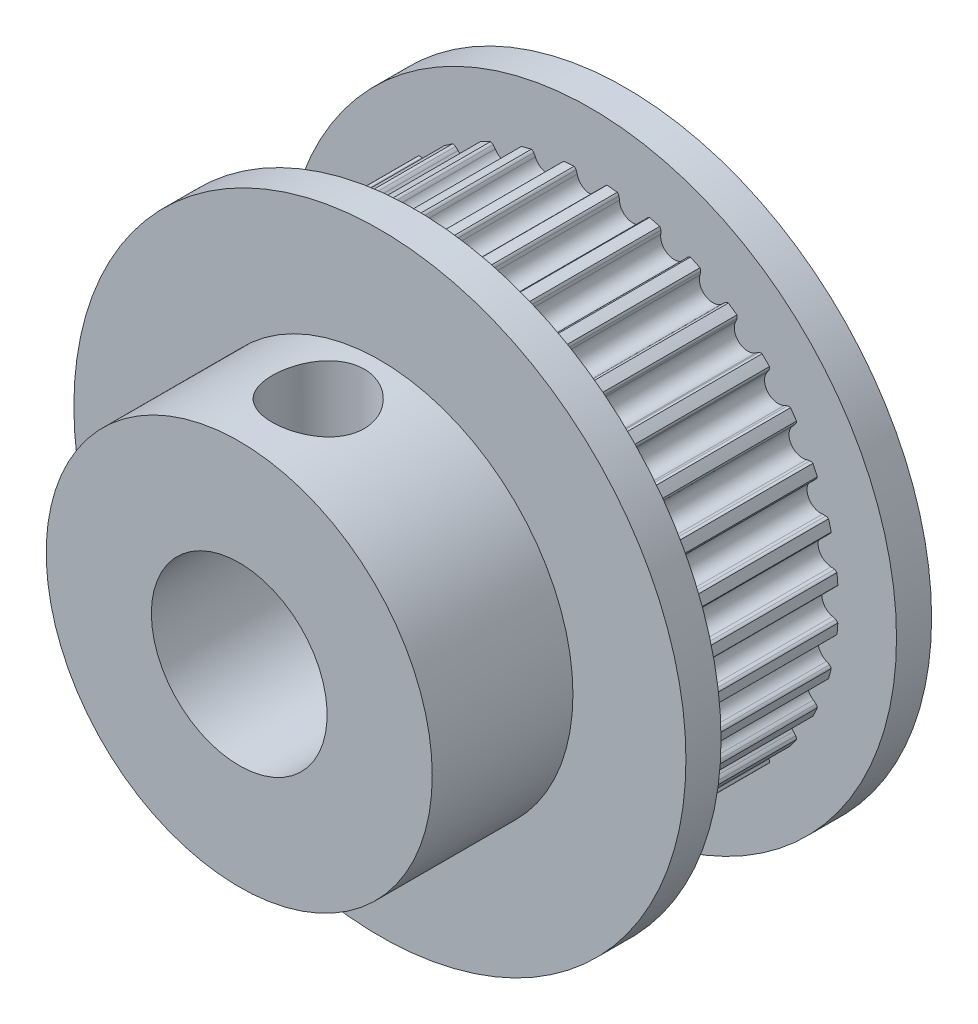
SolidWorks part; units mm, degrees
ref_plane "Front Plane" through (0, 0, 0) normal (0, 0, 1) x (1, 0, 0)
ref_plane "Top Plane" through (0, 0, 0) normal (0, 1, 0) x (1, 0, 0)
ref_plane "Right Plane" through (0, 0, 0) normal (1, 0, 0) x (0, 0, -1)
sketch "Sketch1" plane through (0, 0, 0) normal (0, 1, 0) x (1, 0, 0)
  line L0 (13.843, -3.9687) -> (0, -3.9687)
  line L1 (0, -3.9687) -> (0, -5.5562)
  line L2 (0, -5.5562) -> (13.843, -5.5562)
  line L3 (13.843, -5.5562) -> (13.843, -3.9687)
  line L4 (0, -3.9687) -> (0, -5.5562) construction
revolve "Revolve1" add sketch "Sketch1" angle 360 about L4
sketch "Sketch2" plane through (0, 0, 3.9687) normal (0, 0, -1) x (-1, 0, 0)
  arc A0 (-3.1309, 10.7682) -> (-2.6727, 10.891) centre (0, 0) cw
  arc A6 (-1.2134, 11.1483) -> (-0.7409, 11.1896) centre (0, 0) cw
  arc A7 (-4.5233, 10.2614) -> (-4.4045, 10.2) centre (-4.5654, 10.0341) cw
  arc A8 (-4.4045, 10.2) -> (-4.3083, 10.0819) centre (-4.8573, 9.7334) cw
  arc A9 (-4.3083, 10.0819) -> (-3.1801, 10.4925) centre (-3.7894, 10.4113) ccw
  arc A10 (-3.1801, 10.4925) -> (-3.1824, 10.6448) centre (-2.5356, 10.5784) cw
  arc A11 (-3.1824, 10.6448) -> (-3.1309, 10.7682) centre (-2.9525, 10.6212) cw
  arc A12 (-2.6727, 10.891) -> (-2.5663, 10.8099) centre (-2.7537, 10.6745) cw
  arc A13 (-2.5663, 10.8099) -> (-2.4922, 10.6768) centre (-3.0933, 10.429) cw
  arc A14 (-2.4922, 10.6768) -> (-1.3098, 10.8853) centre (-1.9239, 10.9112) ccw
  arc A15 (-1.3098, 10.8853) -> (-1.2856, 11.0357) centre (-0.6601, 10.858) cw
  arc A16 (-1.2856, 11.0357) -> (-1.2134, 11.1483) centre (-1.0633, 10.9725) cw
  arc A17 (-0.7409, 11.1896) -> (-0.6502, 11.0913) centre (-0.8582, 10.9905) cw
  arc A18 (-0.6502, 11.0913) -> (-0.6003, 10.9474) centre (-1.2354, 10.8077) cw
  arc A19 (-0.6003, 10.9474) -> (0.6003, 10.9474) centre (0, 11.0795) ccw
  arc A20 (0.6003, 10.9474) -> (0.6502, 11.0913) centre (1.2354, 10.8077) cw
  arc A21 (0.6502, 11.0913) -> (0.7409, 11.1896) centre (0.8582, 10.9905) cw
  arc A22 (1.2134, 11.1483) -> (1.2856, 11.0357) centre (1.0633, 10.9725) cw
  arc A23 (1.2856, 11.0357) -> (1.3098, 10.8853) centre (0.6601, 10.858) cw
  arc A24 (1.3098, 10.8853) -> (2.4922, 10.6768) centre (1.9239, 10.9112) ccw
  arc A25 (2.4922, 10.6768) -> (2.5663, 10.8099) centre (3.0933, 10.429) cw
  arc A26 (2.5663, 10.8099) -> (2.6727, 10.891) centre (2.7537, 10.6745) cw
  arc A27 (3.1309, 10.7682) -> (3.1824, 10.6448) centre (2.9525, 10.6212) cw
  arc A28 (3.1824, 10.6448) -> (3.1801, 10.4925) centre (2.5356, 10.5784) cw
  arc A29 (3.1801, 10.4925) -> (4.3083, 10.0819) centre (3.7894, 10.4113) ccw
  arc A30 (4.3083, 10.0819) -> (4.4045, 10.2) centre (4.8573, 9.7334) cw
  arc A31 (4.4045, 10.2) -> (4.5233, 10.2614) centre (4.5654, 10.0341) cw
  arc A32 (4.9532, 10.0609) -> (4.9825, 9.9305) centre (4.752, 9.9471) cw
  arc A33 (4.9825, 9.9305) -> (4.9538, 9.7809) centre (4.334, 9.9774) cw
  arc A34 (4.9538, 9.7809) -> (5.9936, 9.1806) centre (5.5397, 9.5951) ccw
  arc A35 (5.9936, 9.1806) -> (6.1088, 9.2802) centre (6.4737, 8.742) cw
  arc A36 (6.1088, 9.2802) -> (6.2364, 9.32) centre (6.2385, 9.0889) cw
  arc A37 (6.625, 9.048) -> (6.6312, 8.9144) centre (6.4071, 8.9709) cw
  arc A38 (6.6312, 8.9144) -> (6.577, 8.7721) centre (6.0007, 9.0732) cw
  arc A39 (6.577, 8.7721) -> (7.4967, 8.0003) centre (7.1218, 8.4874) ccw
  arc A40 (7.4967, 8.0003) -> (7.6275, 8.0784) centre (7.8934, 7.4851) cw
  arc A41 (7.6275, 8.0784) -> (7.7601, 8.0955) centre (7.722, 7.8675) cw
  arc A42 (8.0955, 7.7601) -> (8.0784, 7.6275) centre (7.8675, 7.722) cw
  arc A43 (8.0784, 7.6275) -> (8.0003, 7.4967) centre (7.4851, 7.8934) cw
  arc A44 (8.0003, 7.4967) -> (8.7721, 6.577) centre (8.4874, 7.1218) ccw
  arc A45 (8.7721, 6.577) -> (8.9144, 6.6312) centre (9.0732, 6.0007) cw
  arc A46 (8.9144, 6.6312) -> (9.048, 6.625) centre (8.9709, 6.4071) cw
  arc A47 (9.32, 6.2364) -> (9.2802, 6.1088) centre (9.0889, 6.2385) cw
  arc A48 (9.2802, 6.1088) -> (9.1806, 5.9936) centre (8.742, 6.4737) cw
  arc A49 (9.1806, 5.9936) -> (9.7809, 4.9538) centre (9.5951, 5.5397) ccw
  arc A50 (9.7809, 4.9538) -> (9.9305, 4.9825) centre (9.9774, 4.334) cw
  arc A51 (9.9305, 4.9825) -> (10.0609, 4.9532) centre (9.9471, 4.752) cw
  arc A52 (10.2614, 4.5233) -> (10.2, 4.4045) centre (10.0341, 4.5654) cw
  arc A53 (10.2, 4.4045) -> (10.0819, 4.3083) centre (9.7334, 4.8573) cw
  arc A54 (10.0819, 4.3083) -> (10.4925, 3.1801) centre (10.4113, 3.7894) ccw
  arc A55 (10.4925, 3.1801) -> (10.6448, 3.1824) centre (10.5784, 2.5356) cw
  arc A56 (10.6448, 3.1824) -> (10.7682, 3.1309) centre (10.6212, 2.9525) cw
  arc A57 (10.891, 2.6727) -> (10.8099, 2.5663) centre (10.6745, 2.7537) cw
  arc A58 (10.8099, 2.5663) -> (10.6768, 2.4922) centre (10.429, 3.0933) cw
  arc A59 (10.6768, 2.4922) -> (10.8853, 1.3098) centre (10.9112, 1.9239) ccw
  arc A60 (10.8853, 1.3098) -> (11.0357, 1.2856) centre (10.858, 0.6601) cw
  arc A61 (11.0357, 1.2856) -> (11.1483, 1.2134) centre (10.9725, 1.0633) cw
  arc A62 (11.1896, 0.7409) -> (11.0913, 0.6502) centre (10.9905, 0.8582) cw
  arc A63 (11.0913, 0.6502) -> (10.9474, 0.6003) centre (10.8077, 1.2354) cw
  arc A64 (10.9474, 0.6003) -> (10.9474, -0.6003) centre (11.0795, 0) ccw
  arc A65 (10.9474, -0.6003) -> (11.0913, -0.6502) centre (10.8077, -1.2354) cw
  arc A66 (11.0913, -0.6502) -> (11.1896, -0.7409) centre (10.9905, -0.8582) cw
  arc A67 (11.1483, -1.2134) -> (11.0357, -1.2856) centre (10.9725, -1.0633) cw
  arc A68 (11.0357, -1.2856) -> (10.8853, -1.3098) centre (10.858, -0.6601) cw
  arc A69 (10.8853, -1.3098) -> (10.6768, -2.4922) centre (10.9112, -1.9239) ccw
  arc A70 (10.6768, -2.4922) -> (10.8099, -2.5663) centre (10.429, -3.0933) cw
  arc A71 (10.8099, -2.5663) -> (10.891, -2.6727) centre (10.6745, -2.7537) cw
  arc A72 (10.7682, -3.1309) -> (10.6448, -3.1824) centre (10.6212, -2.9525) cw
  arc A73 (10.6448, -3.1824) -> (10.4925, -3.1801) centre (10.5784, -2.5356) cw
  arc A74 (10.4925, -3.1801) -> (10.0819, -4.3083) centre (10.4113, -3.7894) ccw
  arc A75 (10.0819, -4.3083) -> (10.2, -4.4045) centre (9.7334, -4.8573) cw
  arc A76 (10.2, -4.4045) -> (10.2614, -4.5233) centre (10.0341, -4.5654) cw
  arc A77 (10.0609, -4.9532) -> (9.9305, -4.9825) centre (9.9471, -4.752) cw
  arc A78 (9.9305, -4.9825) -> (9.7809, -4.9538) centre (9.9774, -4.334) cw
  arc A79 (9.7809, -4.9538) -> (9.1806, -5.9936) centre (9.5951, -5.5397) ccw
  arc A80 (9.1806, -5.9936) -> (9.2802, -6.1088) centre (8.742, -6.4737) cw
  arc A81 (9.2802, -6.1088) -> (9.32, -6.2364) centre (9.0889, -6.2385) cw
  arc A82 (9.048, -6.625) -> (8.9144, -6.6312) centre (8.9709, -6.4071) cw
  arc A83 (8.9144, -6.6312) -> (8.7721, -6.577) centre (9.0732, -6.0007) cw
  arc A84 (8.7721, -6.577) -> (8.0003, -7.4967) centre (8.4874, -7.1218) ccw
  arc A85 (8.0003, -7.4967) -> (8.0784, -7.6275) centre (7.4851, -7.8934) cw
  arc A86 (8.0784, -7.6275) -> (8.0955, -7.7601) centre (7.8675, -7.722) cw
  arc A87 (7.7601, -8.0955) -> (7.6275, -8.0784) centre (7.722, -7.8675) cw
  arc A88 (7.6275, -8.0784) -> (7.4967, -8.0003) centre (7.8934, -7.4851) cw
  arc A89 (7.4967, -8.0003) -> (6.577, -8.7721) centre (7.1218, -8.4874) ccw
  arc A90 (6.577, -8.7721) -> (6.6312, -8.9144) centre (6.0007, -9.0732) cw
  arc A91 (6.6312, -8.9144) -> (6.625, -9.048) centre (6.4071, -8.9709) cw
  arc A92 (6.2364, -9.32) -> (6.1088, -9.2802) centre (6.2385, -9.0889) cw
  arc A93 (6.1088, -9.2802) -> (5.9936, -9.1806) centre (6.4737, -8.742) cw
  arc A94 (5.9936, -9.1806) -> (4.9538, -9.7809) centre (5.5397, -9.5951) ccw
  arc A95 (4.9538, -9.7809) -> (4.9825, -9.9305) centre (4.334, -9.9774) cw
  arc A96 (4.9825, -9.9305) -> (4.9532, -10.0609) centre (4.752, -9.9471) cw
  arc A97 (4.5233, -10.2614) -> (4.4045, -10.2) centre (4.5654, -10.0341) cw
  arc A98 (4.4045, -10.2) -> (4.3083, -10.0819) centre (4.8573, -9.7334) cw
  arc A99 (4.3083, -10.0819) -> (3.1801, -10.4925) centre (3.7894, -10.4113) ccw
  arc A100 (3.1801, -10.4925) -> (3.1824, -10.6448) centre (2.5356, -10.5784) cw
  arc A101 (3.1824, -10.6448) -> (3.1309, -10.7682) centre (2.9525, -10.6212) cw
  arc A102 (2.6727, -10.891) -> (2.5663, -10.8099) centre (2.7537, -10.6745) cw
  arc A103 (2.5663, -10.8099) -> (2.4922, -10.6768) centre (3.0933, -10.429) cw
  arc A104 (2.4922, -10.6768) -> (1.3098, -10.8853) centre (1.9239, -10.9112) ccw
  arc A105 (1.3098, -10.8853) -> (1.2856, -11.0357) centre (0.6601, -10.858) cw
  arc A106 (1.2856, -11.0357) -> (1.2134, -11.1483) centre (1.0633, -10.9725) cw
  arc A107 (0.7409, -11.1896) -> (0.6502, -11.0913) centre (0.8582, -10.9905) cw
  arc A108 (0.6502, -11.0913) -> (0.6003, -10.9474) centre (1.2354, -10.8077) cw
  arc A109 (0.6003, -10.9474) -> (-0.6003, -10.9474) centre (0, -11.0795) ccw
  arc A110 (-0.6003, -10.9474) -> (-0.6502, -11.0913) centre (-1.2354, -10.8077) cw
  arc A111 (-0.6502, -11.0913) -> (-0.7409, -11.1896) centre (-0.8582, -10.9905) cw
  arc A112 (-1.2134, -11.1483) -> (-1.2856, -11.0357) centre (-1.0633, -10.9725) cw
  arc A113 (-1.2856, -11.0357) -> (-1.3098, -10.8853) centre (-0.6601, -10.858) cw
  arc A114 (-1.3098, -10.8853) -> (-2.4922, -10.6768) centre (-1.9239, -10.9112) ccw
  arc A115 (-2.4922, -10.6768) -> (-2.5663, -10.8099) centre (-3.0933, -10.429) cw
  arc A116 (-2.5663, -10.8099) -> (-2.6727, -10.891) centre (-2.7537, -10.6745) cw
  arc A117 (-3.1309, -10.7682) -> (-3.1824, -10.6448) centre (-2.9525, -10.6212) cw
  arc A118 (-3.1824, -10.6448) -> (-3.1801, -10.4925) centre (-2.5356, -10.5784) cw
  arc A119 (-3.1801, -10.4925) -> (-4.3083, -10.0819) centre (-3.7894, -10.4113) ccw
  arc A120 (-4.3083, -10.0819) -> (-4.4045, -10.2) centre (-4.8573, -9.7334) cw
  arc A121 (-4.4045, -10.2) -> (-4.5233, -10.2614) centre (-4.5654, -10.0341) cw
  arc A122 (-4.9532, -10.0609) -> (-4.9825, -9.9305) centre (-4.752, -9.9471) cw
  arc A123 (-4.9825, -9.9305) -> (-4.9538, -9.7809) centre (-4.334, -9.9774) cw
  arc A124 (-4.9538, -9.7809) -> (-5.9936, -9.1806) centre (-5.5397, -9.5951) ccw
  arc A125 (-5.9936, -9.1806) -> (-6.1088, -9.2802) centre (-6.4737, -8.742) cw
  arc A126 (-6.1088, -9.2802) -> (-6.2364, -9.32) centre (-6.2385, -9.0889) cw
  arc A127 (-6.625, -9.048) -> (-6.6312, -8.9144) centre (-6.4071, -8.9709) cw
  arc A128 (-6.6312, -8.9144) -> (-6.577, -8.7721) centre (-6.0007, -9.0732) cw
  arc A129 (-6.577, -8.7721) -> (-7.4967, -8.0003) centre (-7.1218, -8.4874) ccw
  arc A130 (-7.4967, -8.0003) -> (-7.6275, -8.0784) centre (-7.8934, -7.4851) cw
  arc A131 (-7.6275, -8.0784) -> (-7.7601, -8.0955) centre (-7.722, -7.8675) cw
  arc A132 (-8.0955, -7.7601) -> (-8.0784, -7.6275) centre (-7.8675, -7.722) cw
  arc A133 (-8.0784, -7.6275) -> (-8.0003, -7.4967) centre (-7.4851, -7.8934) cw
  arc A134 (-8.0003, -7.4967) -> (-8.7721, -6.577) centre (-8.4874, -7.1218) ccw
  arc A135 (-8.7721, -6.577) -> (-8.9144, -6.6312) centre (-9.0732, -6.0007) cw
  arc A136 (-8.9144, -6.6312) -> (-9.048, -6.625) centre (-8.9709, -6.4071) cw
  arc A137 (-9.32, -6.2364) -> (-9.2802, -6.1088) centre (-9.0889, -6.2385) cw
  arc A138 (-9.2802, -6.1088) -> (-9.1806, -5.9936) centre (-8.742, -6.4737) cw
  arc A139 (-9.1806, -5.9936) -> (-9.7809, -4.9538) centre (-9.5951, -5.5397) ccw
  arc A140 (-9.7809, -4.9538) -> (-9.9305, -4.9825) centre (-9.9774, -4.334) cw
  arc A141 (-9.9305, -4.9825) -> (-10.0609, -4.9532) centre (-9.9471, -4.752) cw
  arc A142 (-10.2614, -4.5233) -> (-10.2, -4.4045) centre (-10.0341, -4.5654) cw
  arc A143 (-10.2, -4.4045) -> (-10.0819, -4.3083) centre (-9.7334, -4.8573) cw
  arc A144 (-10.0819, -4.3083) -> (-10.4925, -3.1801) centre (-10.4113, -3.7894) ccw
  arc A145 (-10.4925, -3.1801) -> (-10.6448, -3.1824) centre (-10.5784, -2.5356) cw
  arc A146 (-10.6448, -3.1824) -> (-10.7682, -3.1309) centre (-10.6212, -2.9525) cw
  arc A147 (-10.891, -2.6727) -> (-10.8099, -2.5663) centre (-10.6745, -2.7537) cw
  arc A148 (-10.8099, -2.5663) -> (-10.6768, -2.4922) centre (-10.429, -3.0933) cw
  arc A149 (-10.6768, -2.4922) -> (-10.8853, -1.3098) centre (-10.9112, -1.9239) ccw
  arc A150 (-10.8853, -1.3098) -> (-11.0357, -1.2856) centre (-10.858, -0.6601) cw
  arc A151 (-11.0357, -1.2856) -> (-11.1483, -1.2134) centre (-10.9725, -1.0633) cw
  arc A152 (-11.1896, -0.7409) -> (-11.0913, -0.6502) centre (-10.9905, -0.8582) cw
  arc A153 (-11.0913, -0.6502) -> (-10.9474, -0.6003) centre (-10.8077, -1.2354) cw
  arc A154 (-10.9474, -0.6003) -> (-10.9474, 0.6003) centre (-11.0795, 0) ccw
  arc A155 (-10.9474, 0.6003) -> (-11.0913, 0.6502) centre (-10.8077, 1.2354) cw
  arc A156 (-11.0913, 0.6502) -> (-11.1896, 0.7409) centre (-10.9905, 0.8582) cw
  arc A157 (-11.1483, 1.2134) -> (-11.0357, 1.2856) centre (-10.9725, 1.0633) cw
  arc A158 (-11.0357, 1.2856) -> (-10.8853, 1.3098) centre (-10.858, 0.6601) cw
  arc A159 (-10.8853, 1.3098) -> (-10.6768, 2.4922) centre (-10.9112, 1.9239) ccw
  arc A160 (-10.6768, 2.4922) -> (-10.8099, 2.5663) centre (-10.429, 3.0933) cw
  arc A161 (-10.8099, 2.5663) -> (-10.891, 2.6727) centre (-10.6745, 2.7537) cw
  arc A162 (-10.7682, 3.1309) -> (-10.6448, 3.1824) centre (-10.6212, 2.9525) cw
  arc A163 (-10.6448, 3.1824) -> (-10.4925, 3.1801) centre (-10.5784, 2.5356) cw
  arc A164 (-10.4925, 3.1801) -> (-10.0819, 4.3083) centre (-10.4113, 3.7894) ccw
  arc A165 (-10.0819, 4.3083) -> (-10.2, 4.4045) centre (-9.7334, 4.8573) cw
  arc A166 (-10.2, 4.4045) -> (-10.2614, 4.5233) centre (-10.0341, 4.5654) cw
  arc A167 (-10.0609, 4.9532) -> (-9.9305, 4.9825) centre (-9.9471, 4.752) cw
  arc A168 (-9.9305, 4.9825) -> (-9.7809, 4.9538) centre (-9.9774, 4.334) cw
  arc A169 (-9.7809, 4.9538) -> (-9.1806, 5.9936) centre (-9.5951, 5.5397) ccw
  arc A170 (-9.1806, 5.9936) -> (-9.2802, 6.1088) centre (-8.742, 6.4737) cw
  arc A171 (-9.2802, 6.1088) -> (-9.32, 6.2364) centre (-9.0889, 6.2385) cw
  arc A172 (-9.048, 6.625) -> (-8.9144, 6.6312) centre (-8.9709, 6.4071) cw
  arc A173 (-8.9144, 6.6312) -> (-8.7721, 6.577) centre (-9.0732, 6.0007) cw
  arc A174 (-8.7721, 6.577) -> (-8.0003, 7.4967) centre (-8.4874, 7.1218) ccw
  arc A175 (-8.0003, 7.4967) -> (-8.0784, 7.6275) centre (-7.4851, 7.8934) cw
  arc A176 (-8.0784, 7.6275) -> (-8.0955, 7.7601) centre (-7.8675, 7.722) cw
  arc A177 (-7.7601, 8.0955) -> (-7.6275, 8.0784) centre (-7.722, 7.8675) cw
  arc A178 (-7.6275, 8.0784) -> (-7.4967, 8.0003) centre (-7.8934, 7.4851) cw
  arc A179 (-7.4967, 8.0003) -> (-6.577, 8.7721) centre (-7.1218, 8.4874) ccw
  arc A180 (-6.577, 8.7721) -> (-6.6312, 8.9144) centre (-6.0007, 9.0732) cw
  arc A181 (-6.6312, 8.9144) -> (-6.625, 9.048) centre (-6.4071, 8.9709) cw
  arc A182 (-6.2364, 9.32) -> (-6.1088, 9.2802) centre (-6.2385, 9.0889) cw
  arc A183 (-6.1088, 9.2802) -> (-5.9936, 9.1806) centre (-6.4737, 8.742) cw
  arc A184 (-5.9936, 9.1806) -> (-4.9538, 9.7809) centre (-5.5397, 9.5951) ccw
  arc A185 (-4.9538, 9.7809) -> (-4.9825, 9.9305) centre (-4.334, 9.9774) cw
  arc A186 (-4.9825, 9.9305) -> (-4.9532, 10.0609) centre (-4.752, 9.9471) cw
  arc A187 (0.7409, 11.1896) -> (1.2134, 11.1483) centre (0, 0) cw
  arc A188 (2.6727, 10.891) -> (3.1309, 10.7682) centre (0, 0) cw
  arc A189 (4.5233, 10.2614) -> (4.9532, 10.0609) centre (0, 0) cw
  arc A190 (6.2364, 9.32) -> (6.625, 9.048) centre (0, 0) cw
  arc A191 (7.7601, 8.0955) -> (8.0955, 7.7601) centre (0, 0) cw
  arc A192 (9.048, 6.625) -> (9.32, 6.2364) centre (0, 0) cw
  arc A193 (10.0609, 4.9532) -> (10.2614, 4.5233) centre (0, 0) cw
  arc A194 (10.7682, 3.1309) -> (10.891, 2.6727) centre (0, 0) cw
  arc A195 (11.1483, 1.2134) -> (11.1896, 0.7409) centre (0, 0) cw
  arc A196 (11.1896, -0.7409) -> (11.1483, -1.2134) centre (0, 0) cw
  arc A197 (10.891, -2.6727) -> (10.7682, -3.1309) centre (0, 0) cw
  arc A198 (10.2614, -4.5233) -> (10.0609, -4.9532) centre (0, 0) cw
  arc A199 (9.32, -6.2364) -> (9.048, -6.625) centre (0, 0) cw
  arc A200 (8.0955, -7.7601) -> (7.7601, -8.0955) centre (0, 0) cw
  arc A201 (6.625, -9.048) -> (6.2364, -9.32) centre (0, 0) cw
  arc A202 (4.9532, -10.0609) -> (4.5233, -10.2614) centre (0, 0) cw
  arc A203 (3.1309, -10.7682) -> (2.6727, -10.891) centre (0, 0) cw
  arc A204 (1.2134, -11.1483) -> (0.7409, -11.1896) centre (0, 0) cw
  arc A205 (-0.7409, -11.1896) -> (-1.2134, -11.1483) centre (0, 0) cw
  arc A206 (-2.6727, -10.891) -> (-3.1309, -10.7682) centre (0, 0) cw
  arc A207 (-4.5233, -10.2614) -> (-4.9532, -10.0609) centre (0, 0) cw
  arc A208 (-6.2364, -9.32) -> (-6.625, -9.048) centre (0, 0) cw
  arc A209 (-7.7601, -8.0955) -> (-8.0955, -7.7601) centre (0, 0) cw
  arc A210 (-9.048, -6.625) -> (-9.32, -6.2364) centre (0, 0) cw
  arc A211 (-10.0609, -4.9532) -> (-10.2614, -4.5233) centre (0, 0) cw
  arc A212 (-10.7682, -3.1309) -> (-10.891, -2.6727) centre (0, 0) cw
  arc A213 (-11.1483, -1.2134) -> (-11.1896, -0.7409) centre (0, 0) cw
  arc A214 (-11.1896, 0.7409) -> (-11.1483, 1.2134) centre (0, 0) cw
  arc A215 (-10.891, 2.6727) -> (-10.7682, 3.1309) centre (0, 0) cw
  arc A216 (-10.2614, 4.5233) -> (-10.0609, 4.9532) centre (0, 0) cw
  arc A217 (-9.32, 6.2364) -> (-9.048, 6.625) centre (0, 0) cw
  arc A218 (-8.0955, 7.7601) -> (-7.7601, 8.0955) centre (0, 0) cw
  arc A219 (-6.625, 9.048) -> (-6.2364, 9.32) centre (0, 0) cw
  arc A220 (-4.9532, 10.0609) -> (-4.5233, 10.2614) centre (0, 0) cw
  point P410 (0, 0)
  dimension "D1" = 36
extrude "Boss-Extrude1" add sketch "Sketch2" along normal blind 7.9375
ref_plane "Plane1" through (0, 0, -3.9688) normal (0, 0, 1) x (1, 0, 0)
sketch "Sketch3" plane through (0, 0, -3.9688) normal (0, 0, 1) x (1, 0, 0)
  circle A0 centre (0, 0) radius 13.843
extrude "Boss-Extrude2" add sketch "Sketch3" against normal blind 1.5875
sketch "Sketch4" plane through (0, 0, 5.5562) normal (0, 0, 1) x (1, 0, 0)
  circle A0 centre (0, 0) radius 8.7312
extrude "Boss-Extrude3" add sketch "Sketch4" along normal blind 6.3627
hole_wizard "M7 Clearance Hole1" positions "Sketch6" profile "Sketch5" hole size "M7" standard "ANSI Metric"
sketch "Sketch6" plane through (0, 0, -5.5562) normal (0, 0, -1) x (-1, 0, 0)
  point P0 (0, 0)
sketch "Sketch5" plane through (0, 0, -5.5562) normal (1, 0, 0) x (0, 1, 0)
  line L0 (0, 0) -> (0, 17.4752)
  line L1 (0, 17.4752) -> (3.9751, 17.4752)
  line L2 (3.9751, 17.4752) -> (3.9751, 0)
  line L5 (3.9751, 0) -> (0, 0)
  line L11 (0, -6.35) -> (0, 107.95) construction
  dimension "Thru Hole Dia." = 7.9502
  dimension "Thru Hole Depth" = 17.4752
ref_plane "Plane2" through (0, 3.3858, 0) normal (0, -1, 0) x (-1, 0, 0)
hole_wizard "M3.5 Clearance Hole1" positions "Sketch8" profile "Sketch7" hole size "M3.5" standard "ANSI Metric"
sketch "Sketch8" plane through (0, 3.3858, 0) normal (0, -1, 0) x (-1, 0, 0)
  point P0 (0, -8.3471)
sketch "Sketch7" plane through (0, 3.3858, 8.3471) normal (1, 0, 0) x (0, 0, -1)
  line L0 (0, 0) -> (0, 10.4572)
  line L1 (0, 10.4572) -> (2.0828, 10.4572)
  line L2 (2.0828, 10.4572) -> (2.0828, 0)
  line L5 (2.0828, 0) -> (0, 0)
  line L11 (0, -6.35) -> (0, 107.95) construction
  dimension "Thru Hole Dia." = 4.1656
  dimension "Thru Hole Depth" = 10.4572
